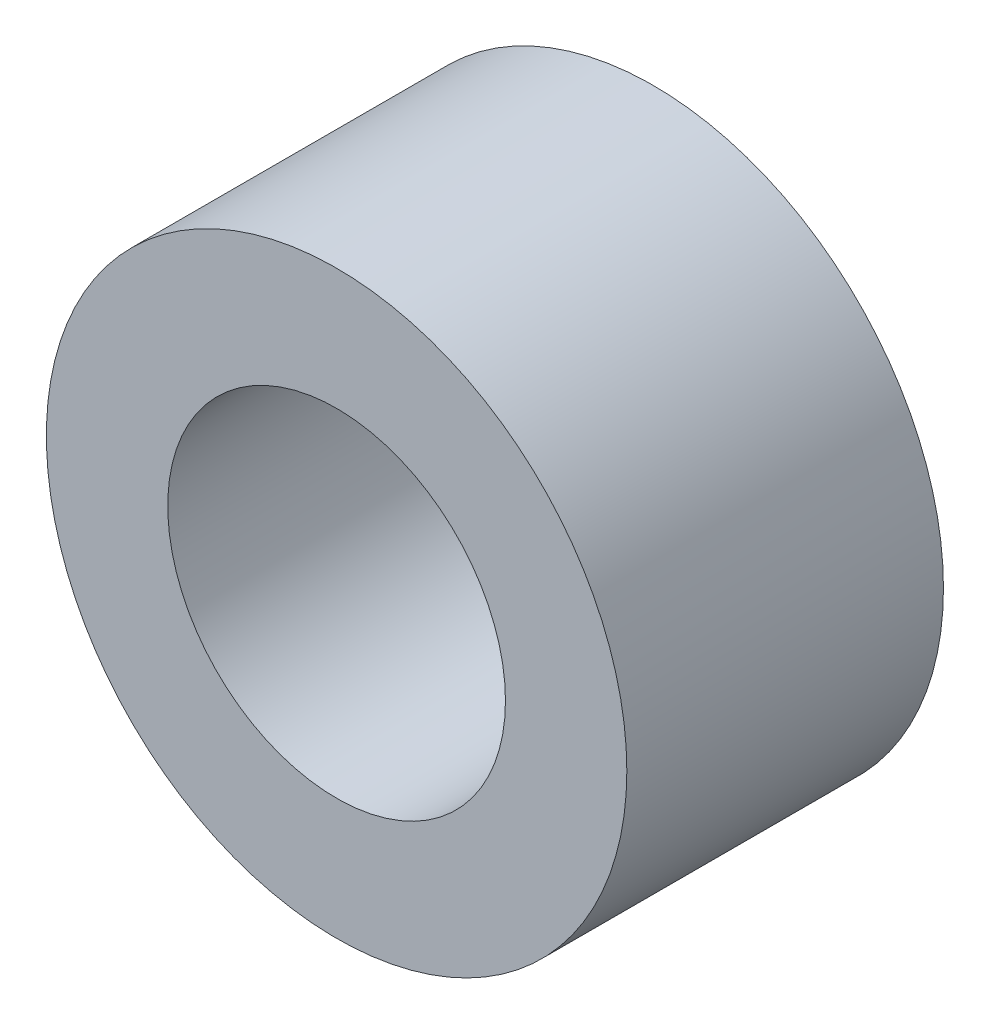
SolidWorks part; units mm, degrees
ref_plane "正面" through (0, 0, 0) normal (0, 0, 1) x (1, 0, 0)
ref_plane "平面" through (0, 0, 0) normal (0, 1, 0) x (1, 0, 0)
ref_plane "右側面" through (0, 0, 0) normal (1, 0, 0) x (0, 0, -1)
sketch "ｽｹｯﾁ1" plane through (0, 0, 0) normal (0, 0, 1) x (1, 0, 0)
  circle A0 centre (0, 0) radius 1.6
  circle A1 centre (0, 0) radius 2.75
  dimension "D1" = 3.2
  dimension "D2" = 5.5
extrude "ﾎﾞｽ - 押し出し1" add sketch "ｽｹｯﾁ1" along normal blind 3
